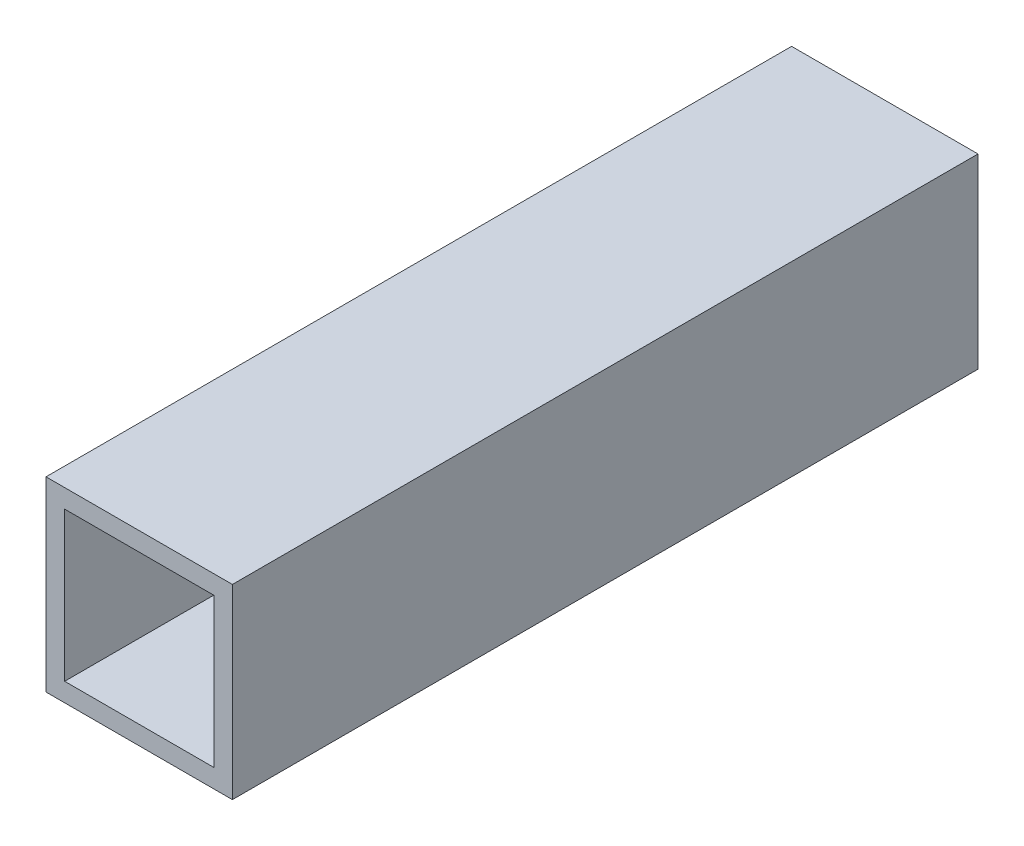
SolidWorks part; units mm, degrees
ref_plane "Front Plane" through (0, 0, 0) normal (0, 0, 1) x (1, 0, 0)
ref_plane "Top Plane" through (0, 0, 0) normal (0, 1, 0) x (1, 0, 0)
ref_plane "Right Plane" through (0, 0, 0) normal (1, 0, 0) x (0, 0, -1)
sketch "Sketch1" plane through (0, 0, 0) normal (0, 0, 1) x (1, 0, 0)
  line L0 (-20, 20) -> (-20, -20)
  line L1 (-25, 25) -> (25, 25)
  line L2 (-25, 25) -> (-25, -25)
  line L3 (-25, -25) -> (25, -25)
  line L4 (25, 25) -> (25, -25)
  line L5 (-20, -20) -> (20, -20)
  line L6 (20, 20) -> (20, -20)
  line L7 (-20, 20) -> (20, 20)
  dimension "tube_width" = 50
  dimension "D1" = 50
  dimension "D3" = 25
  dimension "D4" = 25
  dimension "tube_thickness" = 5
extrude "Boss-Extrude1" add sketch "Sketch1" along normal blind 200
sketch "Sketch3" plane through (25, 0, 0) normal (1, 0, 0) x (0, 0, -1)
  text T0 "<r90>x</r>" font "Century Gothic" height 40
sketch "Sketch4" plane through (25, 0, 0) normal (1, 0, 0) x (0, 0, -1)
  line L0 (0, -25) -> (0, 25) construction
  point P0 (-25, 0)
  dimension "D1" = 25
hole_wizard "Ø25.0mm Dowel Hole1" positions "Sketch5" profile "Sketch6" hole size "Ø25.0" standard "ANSI Metric"
sketch "Sketch5" plane through (25, 0, 0) normal (1, 0, 0) x (0, 0, -1)
  point P0 (50, 0)
sketch "Sketch6" plane through (25, 0, -50) normal (0, 1, 0) x (0, 0, -1)
  line L0 (0, 0) -> (0, 50)
  line L1 (0, 50) -> (12.5, 50)
  line L2 (12.5, 50) -> (12.5, 0)
  line L5 (12.5, 0) -> (0, 0)
  line L11 (0, -6.35) -> (0, 107.95) construction
  dimension "Thru Hole Dia." = 25
  dimension "Thru Hole Depth" = 50
equation "\"D1@Sketch1\"= \"tube_width@Sketch1\""
equation "\"D3@Sketch1\"=\"tube_width@Sketch1\"/2"
equation "\"D4@Sketch1\"=\"tube_width@Sketch1\"/2"
